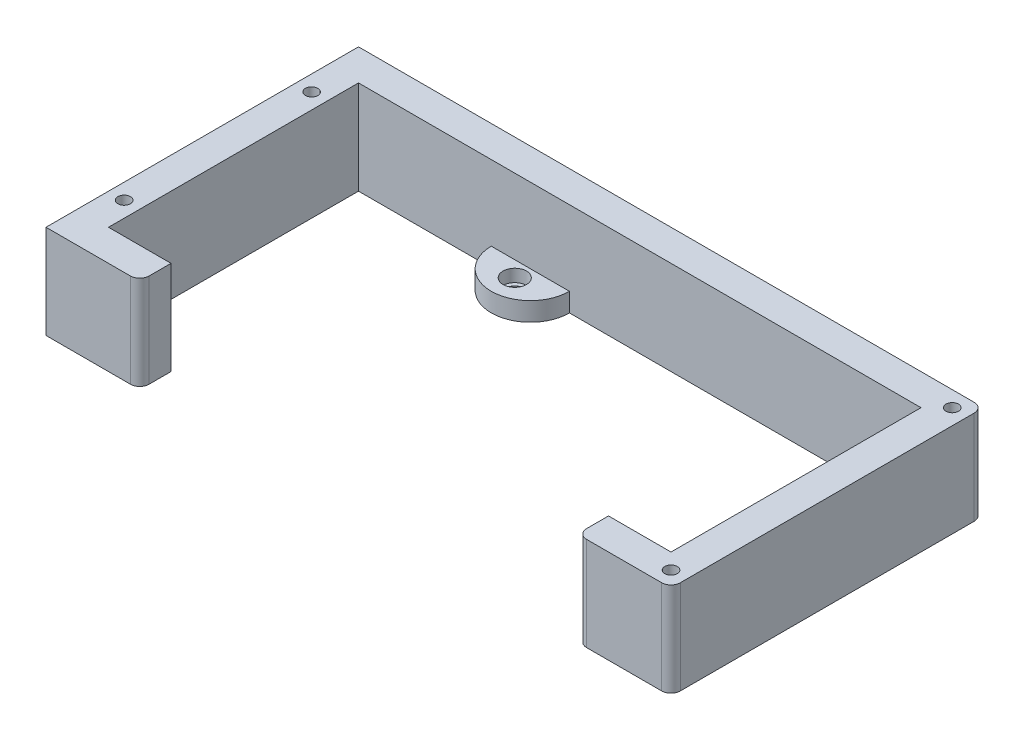
SolidWorks part; units mm, degrees
ref_plane "Front Plane" through (0, 0, 0) normal (0, 0, 1) x (1, 0, 0)
ref_plane "Top Plane" through (0, 0, 0) normal (0, 1, 0) x (1, 0, 0)
ref_plane "Right Plane" through (0, 0, 0) normal (1, 0, 0) x (0, 0, -1)
sketch "Sketch1" plane through (0, 0, 0) normal (0, 1, 0) x (1, 0, 0)
  line L0 (0, 0) -> (-136161.9264, 0) construction
  line L1 (0, 0) -> (0, -136161.9264) construction
  line L2 (-90, 40) -> (-90, -40)
  line L3 (-100, 50) -> (100, 50)
  line L4 (-100, 50) -> (-100, -50)
  line L5 (-100, -50) -> (100, -50)
  line L6 (100, 50) -> (100, -50)
  line L7 (-100, 50) -> (100, -50) construction
  line L8 (-100, -50) -> (100, 50) construction
  line L9 (-90, -40) -> (90, -40)
  line L10 (90, 40) -> (90, -40)
  line L11 (-90, 40) -> (90, 40)
  point P5 (0, 0)
  dimension "D1" = 100
  dimension "D2" = 200
  dimension "D3" = 10
extrude "Boss-Extrude1" add sketch "Sketch1" along normal blind 30
sketch "Sketch2" plane through (0, 0, 0) normal (0, 1, 0) x (1, 0, 0)
  line L0 (0, 0) -> (-50000, 0) construction
  line L1 (0, 0) -> (0, -50000) construction
  line L2 (70, -20) -> (70, 20) construction
  line L3 (70, 20) -> (-70, 20) construction
  line L4 (-70, 20) -> (-70, -20) construction
  line L5 (-70, -20) -> (70, -20) construction
  line L6 (100, -50) -> (100, 50)
  line L7 (100, 50) -> (-100, 50)
  line L8 (-100, 50) -> (-100, -50)
  line L9 (-100, -50) -> (100, -50)
  line L10 (100, -50) -> (100, 50) construction
  line L11 (100, 50) -> (-100, 50) construction
  line L12 (-100, 50) -> (-100, -50) construction
  line L13 (-100, -50) -> (100, -50) construction
  line L14 (70, 20) -> (100, 50) construction
  line L15 (77.5, 40) -> (90, 40)
  line L16 (90, 40) -> (90, 27.5)
  line L17 (90, -40) -> (90, -27.5)
  line L18 (77.5, -40) -> (90, -40)
  line L19 (-35, 35) -> (-35, -49965) construction
  line L20 (90, 40) -> (-90, 40) construction
  line L21 (-47.5, 40) -> (-22.5, 40)
  circle A0 centre (85, 35) radius 2.5
  arc A1 (77.5, 40) -> (90, 27.5) centre (90, 40) ccw
  arc A2 (77.5, -40) -> (90, -27.5) centre (90, -40) cw
  circle A3 centre (85, -35) radius 2.5
  circle A4 centre (-35, 35) radius 2.5
  arc A5 (-47.5, 40) -> (-22.5, 40) centre (-35, 40) ccw
  dimension "D3" = 5
  dimension "D4" = 25
  dimension "D5" = 120
  dimension "D6" = 5
  dimension "D7" = 25
  dimension "D1" = 0
  dimension "D2" = 30
extrude "Boss-Extrude2" add sketch "Sketch2" along normal blind 6
sketch "Sketch3" plane through (0, 6, 0) normal (0, 1, 0) x (1, 0, 0)
  line L0 (0, 0) -> (-50000, 0) construction
  line L1 (0, 0) -> (0, -50000) construction
  circle A0 centre (-35, 35) radius 3.75
  circle A1 centre (85, 35) radius 3.75
  circle A2 centre (85, -35) radius 3.75
  dimension "D1" = 7.5
  dimension "D2" = 7.5
extrude "Cut-Extrude1" cut sketch "Sketch3" against normal blind 4
sketch "Sketch4" plane through (0, 30, 0) normal (0, 1, 0) x (1, 0, 0)
  line L0 (0, 0) -> (-50000, 0) construction
  line L1 (0, 0) -> (0, -50000) construction
  line L2 (90, 40) -> (100, 50) construction
  line L5 (-95, 50) -> (-95, -49950) construction
  line L13 (-100, 50) -> (-100, -50) construction
  line L14 (100, 50) -> (-100, 50) construction
  circle A0 centre (95, 45) radius 2
  circle A1 centre (95, -45) radius 2
  circle A10 centre (-95, 30) radius 2
  circle A11 centre (-95, -30) radius 2
  dimension "D1" = 4
  dimension "D2" = 5
  dimension "D3" = 4
  dimension "D4" = 20
extrude "Cut-Extrude2" cut sketch "Sketch4" against normal blind 15
sketch "Sketch5" plane through (0, 30, 0) normal (0, 1, 0) x (1, 0, 0)
  line L0 (0, 0) -> (-50000, 0) construction
  line L1 (0, 0) -> (0, -50000) construction
  line L2 (95, -45) -> (-49905, -45) construction
  line L3 (-100, -50) -> (100, -50) construction
  line L4 (-70, -40) -> (70, -40)
  line L5 (-70, -40) -> (-70, -50)
  line L6 (-70, -50) -> (70, -50)
  line L7 (70, -40) -> (70, -50)
  line L8 (-70, -40) -> (70, -50) construction
  line L9 (-70, -50) -> (70, -40) construction
  point P8 (0, -45)
  dimension "D1" = 140
extrude "Cut-Extrude3" cut sketch "Sketch5" against normal through all
fillet "Fillet1" radius 3 4 edges at (70, 15, 50) (-70, 15, 50) (100, 15, 50) (100, 15, -50)
